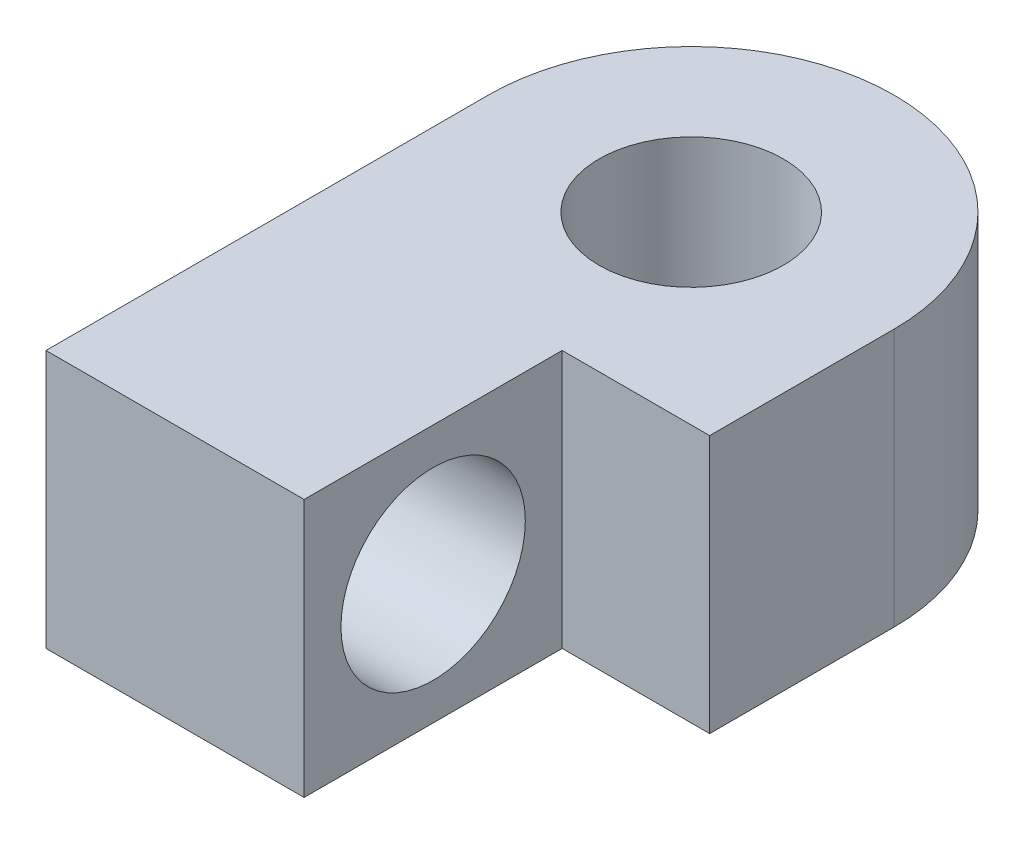
SolidWorks part; units mm, degrees
ref_plane "Alzado" through (0, 0, 0) normal (0, 0, 1) x (1, 0, 0)
ref_plane "Planta" through (0, 0, 0) normal (0, 1, 0) x (1, 0, 0)
ref_plane "Vista lateral" through (0, 0, 0) normal (1, 0, 0) x (0, 0, -1)
sketch "Croquis1" plane through (0, 0, 0) normal (0, 1, 0) x (1, 0, 0)
  line L0 (-5.5, 0) -> (-5.5, -12)
  line L1 (-5.5, -12) -> (1.5, -12)
  line L2 (1.5, -12) -> (1.5, -5)
  line L3 (1.5, -5) -> (5.5, -5)
  line L6 (5.5, -5) -> (5.5, 0)
  circle A0 centre (0, 0) radius 2.5
  arc A1 (5.5, 0) -> (-5.5, 0) centre (0, 0) ccw
  point P3 (7.2222, -12)
  point P9 (3.5, -5)
  point P10 (5.5, -5)
  point P12 (2.503, -5)
  dimension "D1" = 5
  dimension "D2" = 3
  dimension "D3" = 5
  dimension "D4" = 7
  dimension "D5" = 4
extrude "Saliente-Extruir1" add sketch "Croquis1" along normal blind 7
sketch "Croquis3" plane through (-5.5, 0, 0) normal (-1, 0, 0) x (0, 0, 1)
  line L0 (5, 3.5) -> (12, 3.5) construction
  line L1 (5, 7) -> (5, 0) construction
  line L2 (12, 7) -> (12, 0) construction
  circle A0 centre (8.5, 3.5) radius 2.5
  dimension "D1" = 5
extrude "Cortar-Extruir1" cut sketch "Croquis3" against normal blind 17
